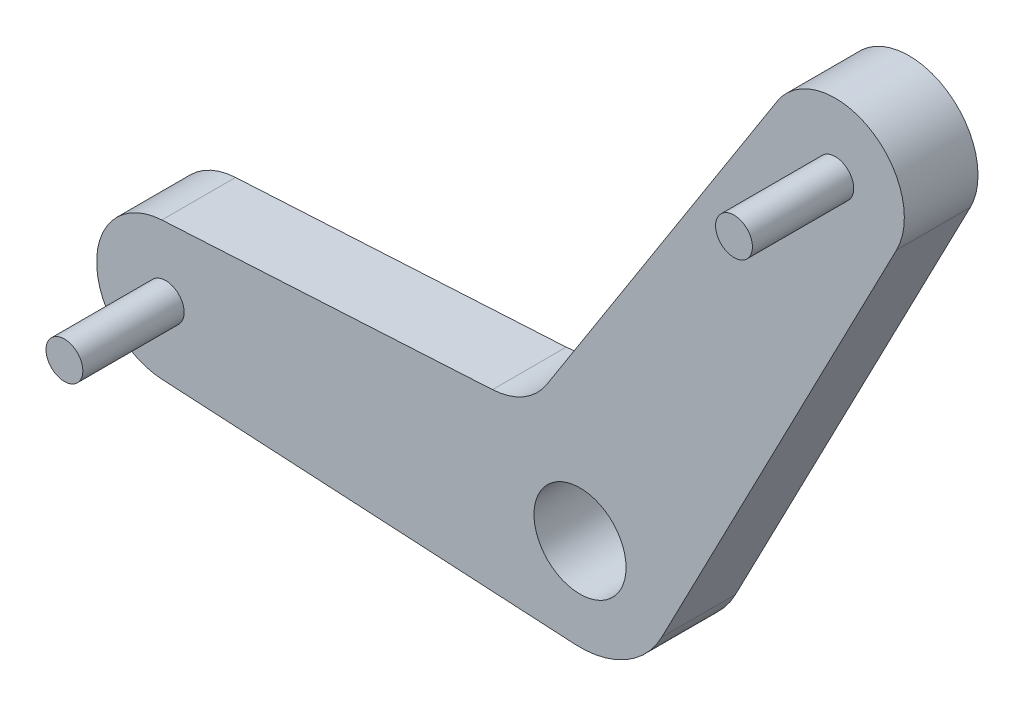
SolidWorks part; units mm, degrees
ref_plane "前视基准面" through (0, 0, 0) normal (0, 0, 1) x (1, 0, 0)
ref_plane "上视基准面" through (0, 0, 0) normal (0, 1, 0) x (1, 0, 0)
ref_plane "右视基准面" through (0, 0, 0) normal (1, 0, 0) x (0, 0, -1)
other "Configuration Table"
sketch "草图1" plane through (0, 0, 0) normal (0, 0, 1) x (1, 0, 0)
  line L0 (-90, 0) -> (0, 0) construction
  line L1 (0, 0) -> (55.45, 96.0422) construction
  line L2 (68.7653, 89.1355) -> (17.7538, -9.2089)
  line L3 (42.811, 104.1203) -> (-7.2002, 25.8722)
  line L4 (-90.8333, 14.9768) -> (-19.0059, 18.9734)
  line L5 (-90.8333, -14.9768) -> (-1.1111, -19.9691)
  arc A0 (-1.1111, -19.9691) -> (17.7538, -9.2089) centre (0, 0) ccw
  arc A1 (68.7653, 89.1355) -> (42.811, 104.1203) centre (55.45, 96.0422) ccw
  arc A2 (-90.8333, 14.9768) -> (-90.8333, -14.9768) centre (-90, 0) ccw
  arc A3 (-7.2002, 25.8722) -> (-19.0059, 18.9734) centre (-19.8392, 33.9503) cw
  dimension "D1" = 15
extrude "凸台-拉伸1" add sketch "草图1" along normal blind 16
sketch "草图2" plane through (0, 0, 16) normal (0, 0, 1) x (1, 0, 0)
  circle A0 centre (-90, 0) radius 4
  circle A1 centre (55.45, 96.0422) radius 4
extrude "凸台-拉伸2" add sketch "草图2" along normal blind 22
sketch "草图3" plane through (0, 0, 0) normal (0, 0, 1) x (1, 0, 0)
  circle A0 centre (0, 0) radius 10
extrude "切除-拉伸1" cut sketch "草图3" along normal blind 16
